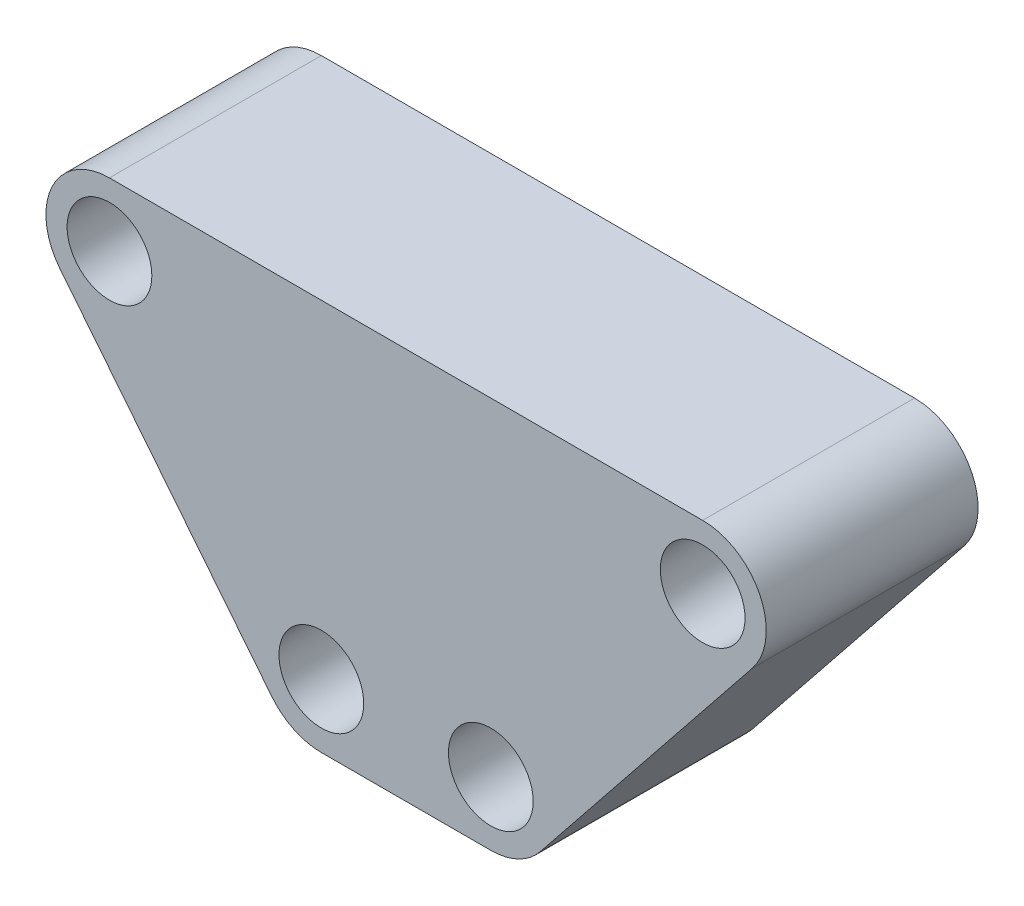
SolidWorks part; units mm, degrees
ref_plane "前视基准面" through (0, 0, 0) normal (0, 0, 1) x (1, 0, 0)
ref_plane "上视基准面" through (0, 0, 0) normal (0, 1, 0) x (1, 0, 0)
ref_plane "右视基准面" through (0, 0, 0) normal (1, 0, 0) x (0, 0, -1)
other "Configuration Table"
sketch "草图1" plane through (0, 0, 0) normal (0, 0, 1) x (1, 0, 0)
  line L0 (0, -7.5) -> (20, -7.5)
  line L3 (50.8547, 26.5375) -> (25.8547, -4.6875)
  line L4 (-30.8547, 26.5375) -> (-5.8547, -4.6875)
  line L5 (-25, 38.725) -> (45, 38.725)
  arc A2 (-5.8547, -4.6875) -> (0, -7.5) centre (0, 0) ccw
  arc A3 (-25, 38.725) -> (-30.8547, 26.5375) centre (-25, 31.225) ccw
  arc A4 (50.8547, 26.5375) -> (45, 38.725) centre (45, 31.225) ccw
  arc A5 (20, -7.5) -> (25.8547, -4.6875) centre (20, 0) ccw
  dimension "D1" = 40
  dimension "D6" = 15
  dimension "D2" = 20
  dimension "D3" = 40
  dimension "D4" = 25
  dimension "D5" = 25
extrude "凸台-拉伸1" add sketch "草图1" along normal blind 25
sketch "草图2" plane through (0, 0, 25) normal (0, 0, 1) x (1, 0, 0)
  circle A0 centre (-25, 31.225) radius 5
  circle A1 centre (0, 0) radius 5
  circle A2 centre (20, 0) radius 5
  circle A3 centre (45, 31.225) radius 5
  dimension "D1" = 10
extrude "切除-拉伸1" cut sketch "草图2" against normal blind 10
